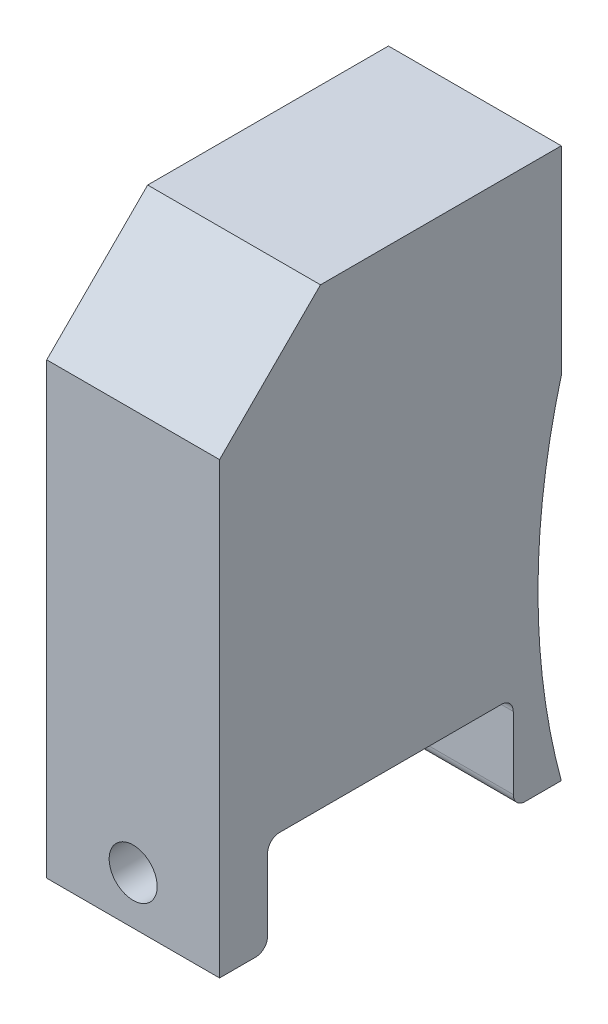
SolidWorks part; units mm, degrees
ref_plane "Front Plane" through (0, 0, 0) normal (0, 0, 1) x (1, 0, 0)
ref_plane "Top Plane" through (0, 0, 0) normal (0, 1, 0) x (1, 0, 0)
ref_plane "Right Plane" through (0, 0, 0) normal (1, 0, 0) x (0, 0, -1)
sketch "Sketch3" plane through (0, 0, 0) normal (1, 0, 0) x (0, 0, -1)
  line L0 (0, 0) -> (-100.3134, 0)
  line L1 (0, 0) -> (0, -82.9443)
  line L2 (-142.3575, -42.044) -> (-142.3575, -229.0796)
  line L3 (-142.3575, -229.0796) -> (0, -229.0796)
  line L6 (-142.3575, -42.044) -> (-100.3134, 0)
  arc A0 (0, -82.9443) -> (0, -229.0796) centre (270.2982, -156.0119) ccw
extrude "Boss-Extrude1" add sketch "Sketch3" along normal blind 72
sketch "Sketch4" plane through (0, 0, 0) normal (0, 0, -1) x (-1, 0, 0)
  circle A0 centre (-36, -41.4721) radius 19.05
extrude "Cut-Extrude1" cut sketch "Sketch4" against normal blind 15
sketch "Sketch5" plane through (0, -229.0796, 0) normal (0, -1, 0) x (1, 0, 0)
  line L3 (0, 0) -> (0, 20)
  line L6 (0, 142.3575) -> (0, 0) construction
  line L7 (0, 142.3575) -> (0, 122.3575)
sketch "Sketch6" plane through (0, 0, 0) normal (-1, 0, 0) x (0, 0, 1)
  line L0 (20, -229.0796) -> (20, -194.0796)
  line L1 (122.3575, -229.0796) -> (122.3575, -194.0796)
  line L2 (117.3575, -189.0796) -> (25, -189.0796)
  arc A0 (20, -194.0796) -> (25, -189.0796) centre (25, -194.0796) cw
  arc A1 (122.3575, -194.0796) -> (117.3575, -189.0796) centre (117.3575, -194.0796) ccw
  dimension "D1" = 5
  dimension "D2" = 5
extrude "Cut-Extrude2" cut sketch "Sketch6" against normal blind 72 and the other way through all
fillet "Fillet2" radius 5 1 edges at (36, -229.0796, 122.3575)
fillet "Fillet3" radius 5 1 edges at (36, -229.0796, 20)
sketch "Sketch7" plane through (0, 0, 20) normal (0, 0, 1) x (1, 0, 0)
  circle A0 centre (36, -209.0796) radius 10
extrude "Cut-Extrude3" cut sketch "Sketch7" against normal blind 20
sketch "Sketch8" plane through (0, 0, 122.3575) normal (0, 0, -1) x (-1, 0, 0)
  circle A0 centre (-36, -209.0796) radius 10
  point P11 (-36, -209.0796)
extrude "Cut-Extrude4" cut sketch "Sketch8" against normal blind 20 contours A0
sketch3d "3DSketch1"
  line L0 (0, -10, 10) -> (0, -81.6196, 10)
  line L1 (0, -179.0796, 25.0019) -> (0, -179.0796, 117.3575)
  line L2 (0, -194.0796, 132.3575) -> (0, -46.1862, 132.3575)
  line L3 (0, -46.1862, 132.3575) -> (0, -10, 96.1713)
  line L4 (0, -10, 96.1713) -> (0, -10, 10)
  line L5 (0, -10, 10) -> (0, -81.6196, 10)
  line L6 (0, -179.0796, 25.0019) -> (0, -179.0796, 117.3575)
  line L7 (0, -194.0796, 132.3575) -> (0, -46.1862, 132.3575)
  line L8 (0, -46.1862, 132.3575) -> (0, -10, 96.1713)
  line L9 (0, -10, 96.1713) -> (0, -10, 10)
  spline S0 degree 5 poles (0, 883.8738, 2845.8593) (0, 378.4227, 1102.3832) (0, 108.4744, 246.441) (0, -5.4062, -21.3342) (0, -45.2672, 1.2056) (0, -88.3206, 11.7144) (0, -91.1628, 12.3616) (0, -99.2415, 14.0955) (0, -107.368, 15.6115) (0, -112.645, 16.485) (0, -125.159, 18.2578) (0, -137.7538, 19.2486) (0, -145.0405, 19.5877) (0, -255.4013, 21.6178) (0, -366.8008, -16.8439) (0, -401.7406, -349.4641) (0, -297.5896, -1240.1757) (0, 15.6502, -2950.3678) knots -2.067628 -2.067628 -2.067628 -2.067628 -2.067628 -2.067628 0.010941 0.010941 0.010941 0.157238 0.157238 0.157238 0.425527 0.425527 0.425527 0.7915 0.7915 0.7915 5.959269 5.959269 5.959269 5.959269 5.959269 5.959269 only from (0, -81.6196, 10) to (0, -180.415, 18.8105)
  spline S1 degree 5 poles (0, 1206.1127, 2667.957) (0, 195.657, 1074.4696) (0, -225.3469, 265.5605) (0, -279.731, -11.4068) (0, -188.8164, -9.035) (0, -179.64, 20.9032) (0, -179.5084, 21.4072) (0, -179.3217, 22.2546) (0, -179.1839, 23.1134) (0, -179.1394, 23.4574) (0, -179.0925, 23.9725) (0, -179.0754, 24.7314) (0, -179.0812, 25.1454) (0, -179.0836, 25.5593) (0, -179.0649, 25.9729) (0, -3171.2185, 79.6762) knots -23.957377 -23.957377 -23.957377 -23.957377 -23.957377 -23.957377 0.186963 0.186963 0.186963 0.594974 0.594974 0.594974 0.865886 0.865886 0.865886 0.9997 1.19054 1.19054 1.19054 1.19054 1.19054 1.19054 only from (0, -180.415, 18.8105) to (0, -179.0796, 25.0019)
  spline S2 degree 5 poles (0, 2820.5339, 119.0125) (0, 991.0516, 96.4812) (0, 91.4128, 90.871) (0, -193.4475, 96.4482) (0, -178.1119, 107.8377) (0, -179.1417, 118.9293) (0, -179.1876, 119.2775) (0, -179.329, 120.1444) (0, -179.5204, 120.9994) (0, -179.6548, 121.5069) (0, -179.9661, 122.5088) (0, -180.369, 123.4793) (0, -180.5923, 123.9555) (0, -181.0802, 124.8872) (0, -181.6464, 125.7727) (0, -181.9485, 126.2028) (0, -182.5893, 127.0355) (0, -183.3009, 127.8091) (0, -183.6734, 128.18) (0, -184.4499, 128.8884) (0, -185.2854, 129.5257) (0, -185.7167, 129.826) (0, -186.6046, 130.3885) (0, -187.5383, 130.8724) (0, -188.0155, 131.0937) (0, -188.9838, 131.4909) (0, -189.9828, 131.7971) (0, -190.4868, 131.9287) (0, -191.3342, 132.1154) (0, -192.193, 132.2532) (0, -192.537, 132.2977) (0, -203.5419, 133.2992) (0, -214.8361, 118.2206) (0, -220.3835, 403.3294) (0, -214.8736, 1302.9565) (0, -192.6416, 3131.906) knots -2.24929 -2.24929 -2.24929 -2.24929 -2.24929 -2.24929 0.037136 0.037136 0.037136 0.111408 0.111408 0.111408 0.222815 0.222815 0.222815 0.334223 0.334223 0.334223 0.445631 0.445631 0.445631 0.557039 0.557039 0.557039 0.668446 0.668446 0.668446 0.779854 0.779854 0.779854 0.890372 0.890372 0.890372 0.963754 0.963754 0.963754 3.232473 3.232473 3.232473 3.232473 3.232473 3.232473 only from (0, -179.0796, 117.3575) to (0, -194.0796, 132.3575)
  spline S3 degree 5 poles (0, -81.6196, 10) (0, -81.8301, 10.0565) (0, -82.0406, 10.1128) (0, -82.2511, 10.1689) (0, -85.2779, 10.9717) (0, -88.3206, 11.7144) (0, -91.1628, 12.3616) (0, -99.2415, 14.0955) (0, -107.368, 15.6115) (0, -112.645, 16.485) (0, -125.159, 18.2578) (0, -137.7538, 19.2486) (0, -145.0405, 19.5877) (0, -156.4974, 19.7984) (0, -167.9654, 19.5728) (0, -172.1245, 19.4162) (0, -176.2759, 19.1679) (0, -180.415, 18.8105) knots 0 0 0 0 0 0 0.010941 0.010941 0.010941 0.157238 0.157238 0.157238 0.425527 0.425527 0.425527 0.7915 0.7915 0.7915 1 1 1 1 1 1
  spline S4 degree 5 poles (0, -180.415, 18.8105) (0, -180.3164, 19.0279) (0, -180.2223, 19.2473) (0, -180.1327, 19.4684) (0, -179.8623, 20.1777) (0, -179.64, 20.9032) (0, -179.5084, 21.4072) (0, -179.3217, 22.2546) (0, -179.1839, 23.1134) (0, -179.1394, 23.4574) (0, -179.0925, 23.9725) (0, -179.0809, 24.4886) (0, -179.0796, 24.6596) (0, -179.0796, 24.8306) (0, -179.0796, 25.0015) (0, -179.0796, 25.0019) knots 0 0 0 0 0 0 0.186963 0.186963 0.186963 0.594974 0.594974 0.594974 0.865886 0.865886 0.865886 0.9997 1 1 1 1 1 1
  spline S5 degree 5 poles (0, -179.0796, 117.3575) (0, -179.0796, 117.5323) (0, -179.0796, 117.707) (0, -179.081, 117.8818) (0, -179.0931, 118.4059) (0, -179.1417, 118.9293) (0, -179.1876, 119.2775) (0, -179.329, 120.1444) (0, -179.5204, 120.9994) (0, -179.6548, 121.5069) (0, -179.9661, 122.5088) (0, -180.369, 123.4793) (0, -180.5923, 123.9555) (0, -181.0802, 124.8872) (0, -181.6464, 125.7727) (0, -181.9485, 126.2028) (0, -182.5893, 127.0355) (0, -183.3009, 127.8091) (0, -183.6734, 128.18) (0, -184.4499, 128.8884) (0, -185.2854, 129.5257) (0, -185.7167, 129.826) (0, -186.6046, 130.3885) (0, -187.5383, 130.8724) (0, -188.0155, 131.0937) (0, -188.9838, 131.4909) (0, -189.9828, 131.7971) (0, -190.4868, 131.9287) (0, -191.3342, 132.1154) (0, -192.193, 132.2532) (0, -192.537, 132.2977) (0, -193.0521, 132.3445) (0, -193.5679, 132.3562) (0, -193.7384, 132.3575) (0, -193.909, 132.3575) (0, -194.0796, 132.3575) knots 0 0 0 0 0 0 0.037136 0.037136 0.037136 0.111408 0.111408 0.111408 0.222815 0.222815 0.222815 0.334223 0.334223 0.334223 0.445631 0.445631 0.445631 0.557039 0.557039 0.557039 0.668446 0.668446 0.668446 0.779854 0.779854 0.779854 0.890372 0.890372 0.890372 0.963754 0.963754 0.963754 1 1 1 1 1 1
  dimension "D1" = 10
extrude "Cut-Extrude5" cut sketch "3DSketch1" along direction (1, 0, 0) on the side of the normal blind 62 and the other way through all
